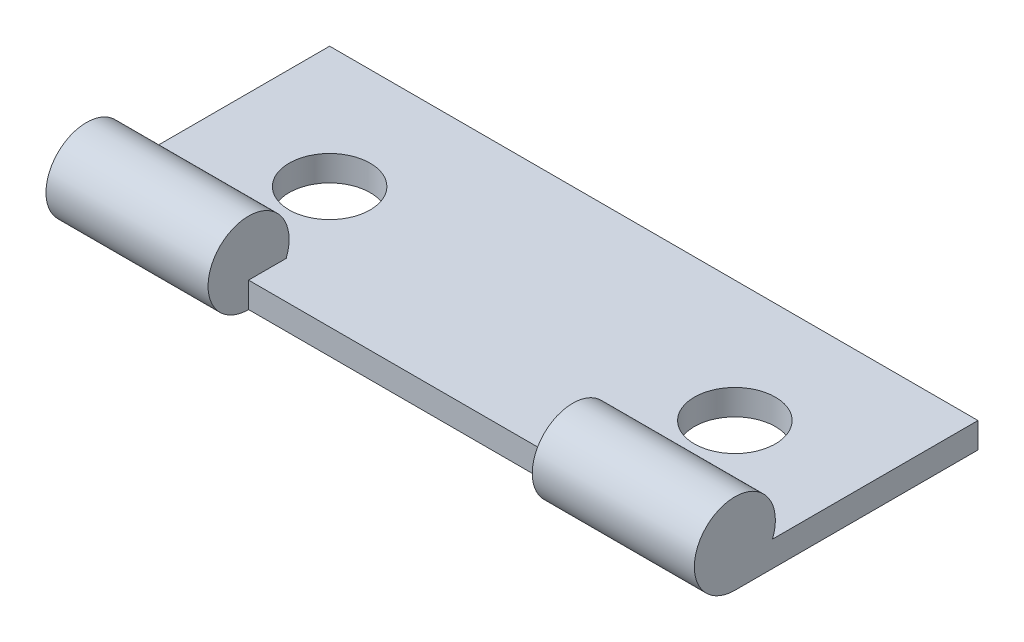
SolidWorks part; units mm, degrees
material "Bronce al estaño"
ref_plane "Front Plane" through (0, 0, 0) normal (0, 0, 1) x (1, 0, 0)
ref_plane "Top Plane" through (0, 0, 0) normal (0, 1, 0) x (1, 0, 0)
ref_plane "Right Plane" through (0, 0, 0) normal (1, 0, 0) x (0, 0, -1)
sketch "Sketch1" plane through (0, 0, 0) normal (0, 1, 0) x (1, 0, 0)
  line L0 (12.7, 9.525) -> (12.7, 0) construction
  line L1 (0, 0) -> (25.4, 0)
  line L2 (0, 0) -> (0, 9.525)
  line L3 (0, 9.525) -> (25.4, 9.525)
  line L4 (25.4, 0) -> (25.4, 9.525)
  circle A0 centre (4.7625, 4.7625) radius 1.5875
  circle A1 centre (20.6375, 4.7625) radius 1.5875
  dimension "D3" = 3.175
  dimension "D1" = 9.525
  dimension "D2" = 25.4
  dimension "D4" = 4.7625
  dimension "D5" = 4.7625
extrude "Boss-Extrude1" add sketch "Sketch1" along normal blind 1
sketch "Sketch2" plane through (0, 0, 0) normal (-1, 0, 0) x (0, 0, 1)
  line L0 (0, 0) -> (0, 1.5875) construction
  line L1 (0, 1) -> (0, 0) construction
  circle A0 centre (0, 1.5875) radius 1.5875
  dimension "D1" = 1.5875
extrude "Boss-Extrude2" add sketch "Sketch2" against normal blind 6.35
pattern_linear "LPattern1" count 2 spacing 19.05 along (1, 0, 0) of "Boss-Extrude2"
